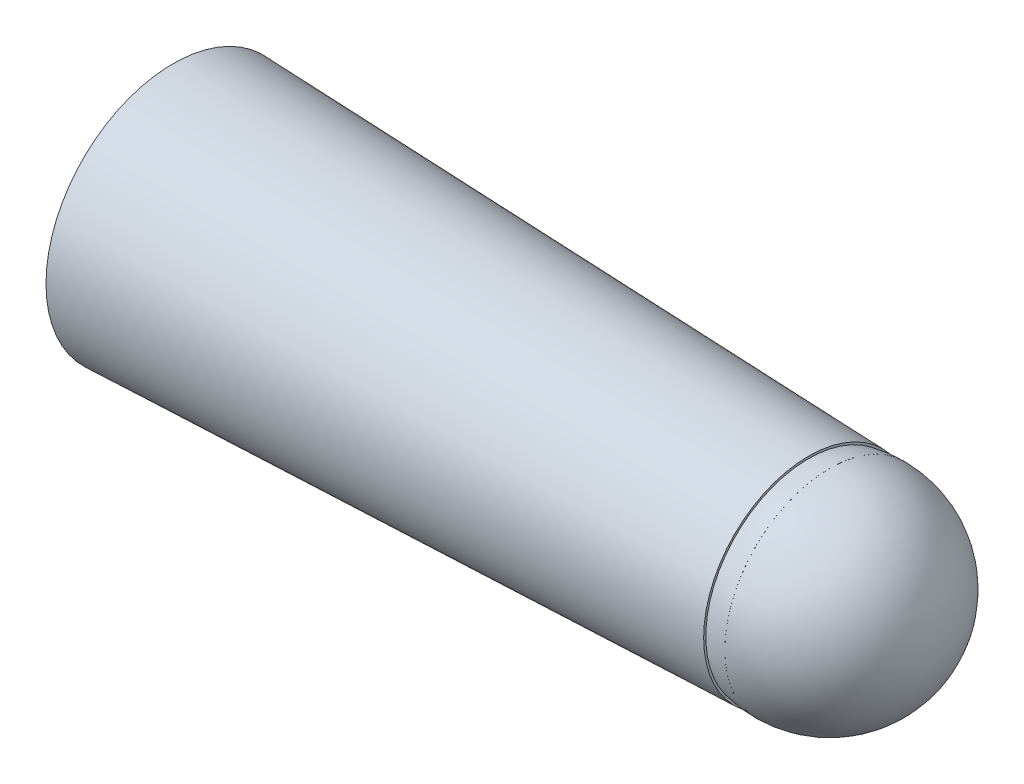
SolidWorks part; units mm, degrees
material "Cast Alloy Steel"
ref_plane "Front Plane" through (0, 0, 0) normal (0, 0, 1) x (1, 0, 0)
ref_plane "Top Plane" through (0, 0, 0) normal (0, 1, 0) x (1, 0, 0)
ref_plane "Right Plane" through (0, 0, 0) normal (1, 0, 0) x (0, 0, -1)
sketch "Sketch1" plane through (0, 0, 0) normal (1, 0, 0) x (0, 0, -1)
  circle A0 centre (0, 0) radius 3
  dimension "D1" = 6
extrude "Boss-Extrude1" add sketch "Sketch1" along normal blind 15 draft 2
surface "Surface-Offset1" parameters "D1"=0.5
sketch "Sketch2" plane through (15.5, 0, 0) normal (1, 0, 0) x (0, 0, -1)
  line L0 (0, 2.4762) -> (0, -2.4762) construction
  line L1 (0, 2.4762) -> (0, -2.4762)
  arc A0 (0, -2.4762) -> (0, 2.4762) centre (0, 0) ccw
  circle A1 centre (0, 0) radius 2.4762 construction
  dimension "D1" = 2.4762
revolve "Revolve1" add sketch "Sketch2" angle 360 about L0
